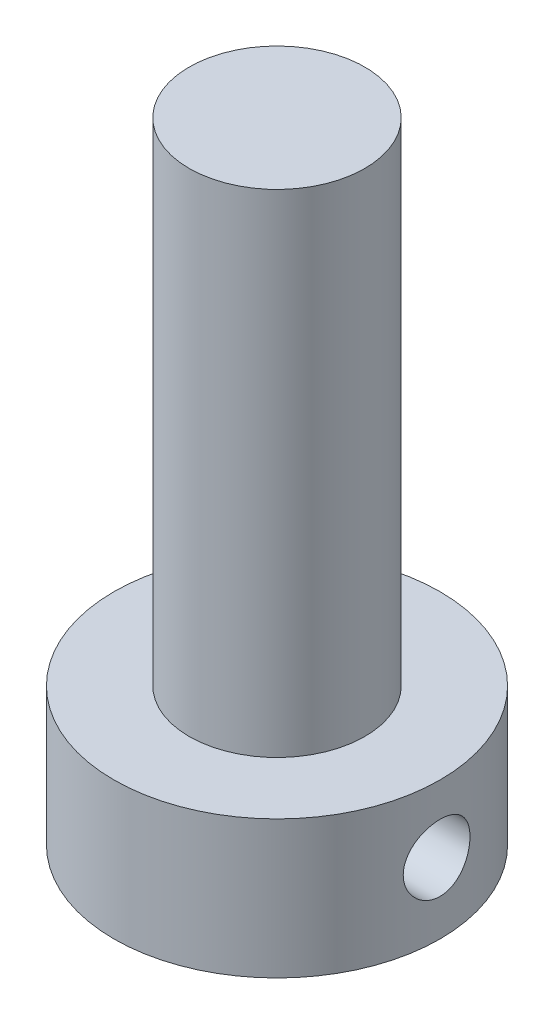
SolidWorks part; units mm, degrees
ref_plane "Front Plane" through (0, 0, 0) normal (0, 0, 1) x (1, 0, 0)
ref_plane "Top Plane" through (0, 0, 0) normal (0, 1, 0) x (1, 0, 0)
ref_plane "Right Plane" through (0, 0, 0) normal (1, 0, 0) x (0, 0, -1)
sketch "Sketch2" plane through (0, 0, 0) normal (0, 1, 0) x (1, 0, 0)
  circle A0 centre (0, 0) radius 11.6
  dimension "D1" = 23.2
extrude "Boss-Extrude1" add sketch "Sketch2" along normal blind 9.8
ref_plane "Plane4" through (11.6, 0, 0) normal (1, 0, 0) x (0, 0, -1)
sketch "Sketch3" plane through (11.6, 0, 0) normal (1, 0, 0) x (0, 0, -1)
  circle A0 centre (0, 5) radius 2.375
  dimension "D1" = 4.75
  dimension "D2" = 5
sketch "Sketch7" plane through (0, 9.8, 0) normal (0, 1, 0) x (1, 0, 0)
  circle A0 centre (0, 0) radius 6.25
  dimension "D1" = 12.5
extrude "Boss-Extrude3" add sketch "Sketch7" along normal blind 35
extrude "Cut-Extrude1" cut sketch "Sketch3" against normal blind 5
scale "Scale1" scale about centroid uniform scaling yes scale factor 0.8
